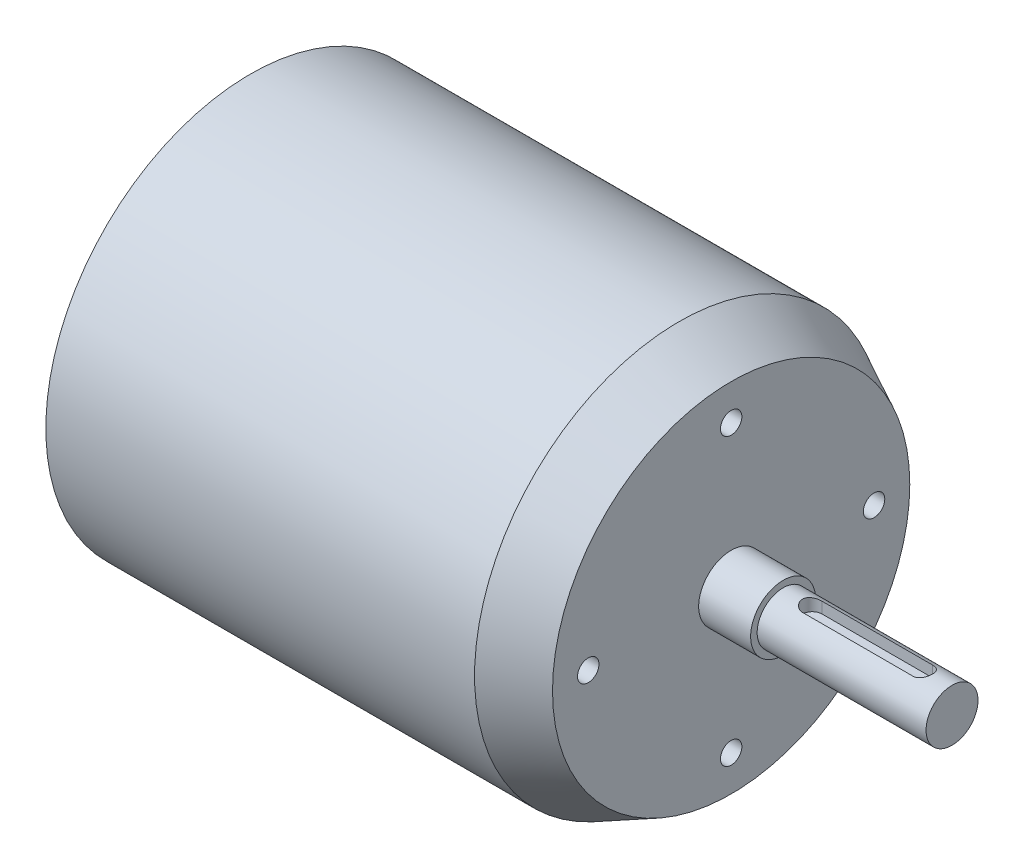
SolidWorks part; units mm, degrees
ref_plane "Front" through (0, 0, 0) normal (0, 0, 1) x (1, 0, 0)
ref_plane "Top" through (0, 0, 0) normal (0, 1, 0) x (1, 0, 0)
ref_plane "Right" through (0, 0, 0) normal (1, 0, 0) x (0, 0, -1)
sketch "草图1" plane through (0, 0, 0) normal (1, 0, 0) x (0, 0, -1)
  circle A0 centre (0, 0) radius 31.5
extrude "凸台-拉伸1" add sketch "草图1" against normal blind 74
sketch "草图2" plane through (0, 0, 0) normal (1, 0, 0) x (0, 0, -1)
  circle A0 centre (0, 0) radius 5
extrude "凸台-拉伸2" add sketch "草图2" along normal blind 8
sketch "草图3" plane through (8, 0, 0) normal (1, 0, 0) x (0, 0, -1)
  circle A0 centre (0, 0) radius 4
extrude "凸台-拉伸3" add sketch "草图3" along normal blind 26
sketch3d "3D草图1"
  line L0 (34, 4, 0) -> (31, 4, 0) construction
  line L1 (31, 4, 0) -> (29.5, 4, 0) construction
  line L2 (8, 4, 0) -> (11, 4, 0) construction
  line L3 (11, 4, 0) -> (12.5, 4, 0) construction
  line L4 (12.5, 4, 1.5) -> (29.5, 4, 1.5)
  line L5 (12.5, 4, -1.5) -> (29.5, 4, -1.5)
  circle A0 centre (34, 0, 0) radius 4 construction
  arc A1 (29.5, 4, 1.5) -> (29.5, 4, -1.5) centre (29.5, 4, 0) ccw
  circle A2 centre (8, 0, 0) radius 4 construction
  arc A3 (12.5, 4, -1.5) -> (12.5, 4, 1.5) centre (12.5, 4, 0) ccw
  point P4 (38, 0, 0)
  point P7 (29.5, 5.5, 0)
  point P12 (12, 0, 0)
  point P15 (12.5, 5.5, 0)
  dimension "D1" = 4
extrude "切除-拉伸1" cut sketch "3D草图1" along direction (0, 1, 0) on the side of the normal blind 2
sketch "草图5" plane through (0, 0, 0) normal (1, 0, 0) x (0, 0, -1)
  circle A0 centre (0, 0) radius 22 construction
  circle A1 centre (0, 22) radius 2 construction
  circle A2 centre (-22, 0) radius 2 construction
  circle A3 centre (0, -22) radius 2 construction
  circle A4 centre (22, 0) radius 2 construction
hole_wizard "M4x0.7 螺纹孔1" positions "3D草图3" profile "草图7" tap size "M4x0.7" standard "ANSI Metric"
sketch3d "3D草图3"
  point P0 (0, 22, 0)
  point P3 (0, 0, -22)
  point P6 (0, -22, 0)
  point P9 (0, 0, 22)
sketch "草图7" plane through (0, 22, 0) normal (0, 1, 0) x (0, 0, -1)
  line L0 (0, 0) -> (0, 11.0914)
  line L1 (0, 11.0914) -> (1.65, 10.1)
  line L2 (1.65, 10.1) -> (1.65, 0)
  line L5 (1.65, 0) -> (0, 0)
  line L10 (0, 11.0914) -> (-1.65, 10.1) construction
  line L11 (0, -6.35) -> (0, 107.95) construction
  dimension "螺纹孔钻头直径" = 3.3
  dimension "螺纹孔钻头深度" = 10.1
  dimension "导头角度" = 118
cosmetic thread "孔螺蚊线1" parameters "D1"=8, "D2"=4
cosmetic thread "孔螺蚊线2" parameters "D1"=8, "D2"=4
cosmetic thread "孔螺蚊线3" parameters "D1"=8, "D2"=4
cosmetic thread "孔螺蚊线4" parameters "D1"=8, "D2"=4
sketch "草图9" plane through (0, 0, 0) normal (0, 0, 1) x (1, 0, 0)
  line L0 (0, 31.5) -> (0, 27.5)
  line L1 (0, -31.5) -> (0, 31.5) construction
  line L2 (0, 31.5) -> (-8, 31.5)
  line L3 (0, 31.5) -> (-74, 31.5) construction
  line L4 (-8, 31.5) -> (0, 27.5)
  line L5 (0, 0) -> (-10, 0) construction
revolve "切除-旋转1" cut sketch "草图9" angle 360 about L5
